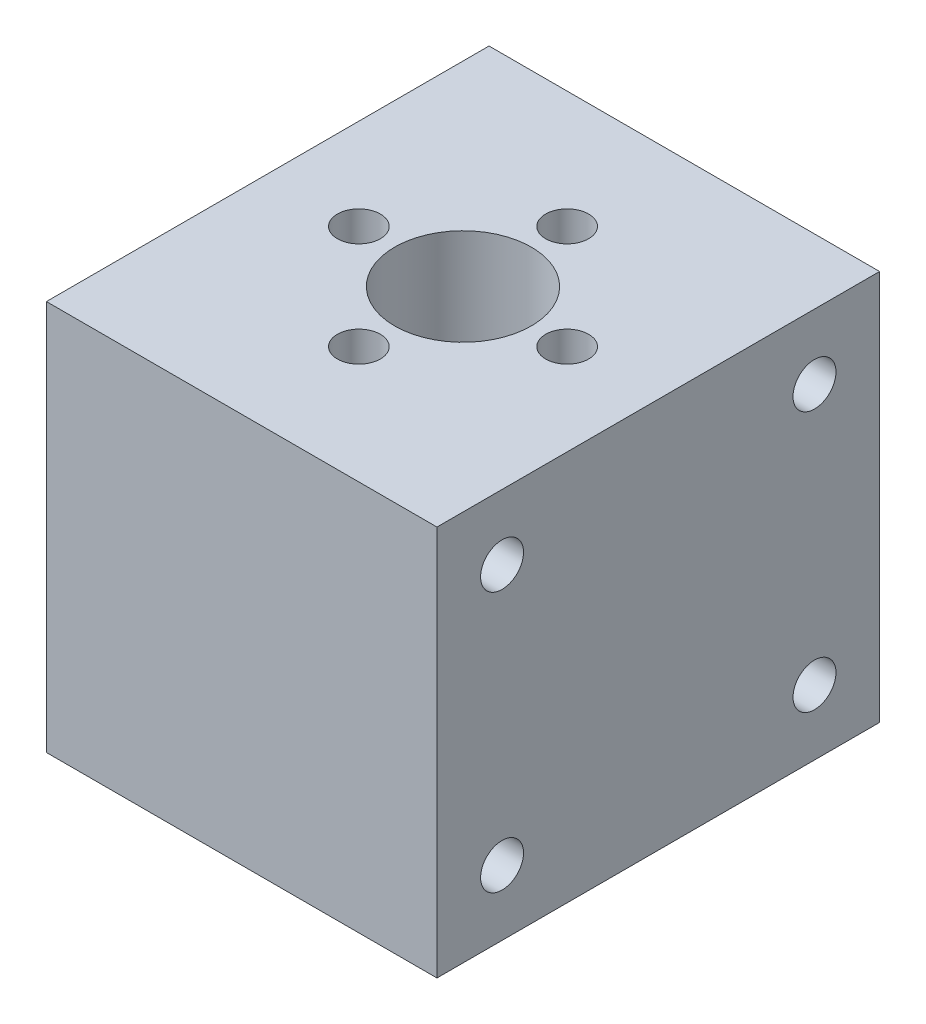
SolidWorks part; units mm, degrees
material "6061-O (SS)"
ref_plane "前视基准面" through (0, 0, 0) normal (0, 0, 1) x (1, 0, 0)
ref_plane "上视基准面" through (0, 0, 0) normal (0, 1, 0) x (1, 0, 0)
ref_plane "右视基准面" through (0, 0, 0) normal (1, 0, 0) x (0, 0, -1)
sketch "草图1" plane through (0, 0, 0) normal (0, 1, 0) x (1, 0, 0)
  line L1 (0, 0) -> (30, 0)
  line L2 (0, 0) -> (0, 34)
  line L3 (0, 34) -> (30, 34)
  line L4 (30, 0) -> (30, 34)
  dimension "D1" = 30
  dimension "D2" = 34
extrude "凸台-拉伸1" add sketch "草图1" along normal blind 30
sketch "草图2" plane through (30, 0, 0) normal (1, 0, 0) x (0, 0, -1)
  line L0 (0, 0) -> (34, 0) construction
  line L1 (0, 30) -> (34, 30) construction
  line L2 (34, 30) -> (34, 0) construction
  line L3 (0, 30) -> (0, 0) construction
  point P0 (5, 25)
  point P1 (29, 25)
  point P2 (5, 5)
  point P3 (29, 5)
  dimension "D1" = 5
  dimension "D2" = 5
  dimension "D3" = 5
  dimension "D4" = 5
  dimension "D5" = 5
  dimension "D6" = 5
  dimension "D7" = 5
  dimension "D8" = 5
hole_wizard "孔1" positions "草图2" profile "草图3" legacy
sketch "草图3" plane through (30, 25, -5) normal (0, 1, 0) x (0, 0, -1)
  line L0 (0, 0) -> (0, 10)
  line L1 (0, 10) -> (1.65, 10)
  line L2 (1.65, 10) -> (1.65, 0)
  line L3 (1.65, 0) -> (0, 0)
  line L4 (0, 110) -> (0, -10) construction
  dimension "直径" = 3.3
  dimension "深度" = 10
sketch "草图4" plane through (0, 30, 0) normal (0, 1, 0) x (1, 0, 0)
  line L0 (0, 0) -> (30, 34)
  line L2 (7, 25) -> (23, 25)
  line L3 (7, 25) -> (7, 9)
  line L4 (7, 9) -> (23, 9)
  line L5 (23, 25) -> (23, 9)
  line L6 (7, 25) -> (23, 9) construction
  line L7 (7, 9) -> (23, 25) construction
  circle A0 centre (15, 17) radius 5.25
  dimension "D1" = 10.5
  dimension "D2" = 16
  dimension "D3" = 16
sketch "草图5" plane through (0, 30, 0) normal (0, 1, 0) x (1, 0, 0)
  line L0 (7, 25) -> (7, 9) construction
  line L1 (7, 25) -> (23, 25) construction
  line L2 (23, 25) -> (23, 9) construction
  line L3 (7, 9) -> (23, 9) construction
  point P0 (7, 17)
  point P4 (15, 25)
  point P8 (23, 17)
  point P12 (15, 9)
hole_wizard "孔2" positions "草图5" profile "草图6" legacy
sketch "草图6" plane through (7, 30, -17) normal (1, 0, 0) x (0, 0, 1)
  line L0 (0, 0) -> (0, 10)
  line L1 (0, 10) -> (1.65, 10)
  line L2 (1.65, 10) -> (1.65, 0)
  line L3 (1.65, 0) -> (0, 0)
  line L4 (0, 110) -> (0, -10) construction
  dimension "直径" = 3.3
  dimension "深度" = 10
sketch "草图7" plane through (0, 30, 0) normal (0, 1, 0) x (1, 0, 0)
  point P0 (15, 17)
hole_wizard "孔3" positions "草图7" profile "草图8" legacy end condition up to next
sketch "草图8" plane through (15, 30, -17) normal (1, 0, 0) x (0, 0, 1)
  line L0 (0, 0) -> (0, 30)
  line L1 (0, 30) -> (5.25, 30)
  line L2 (5.25, 30) -> (5.25, 0)
  line L3 (5.25, 0) -> (0, 0)
  line L4 (0, 110) -> (0, -10) construction
  dimension "直径" = 10.5
  dimension "深度" = 30
